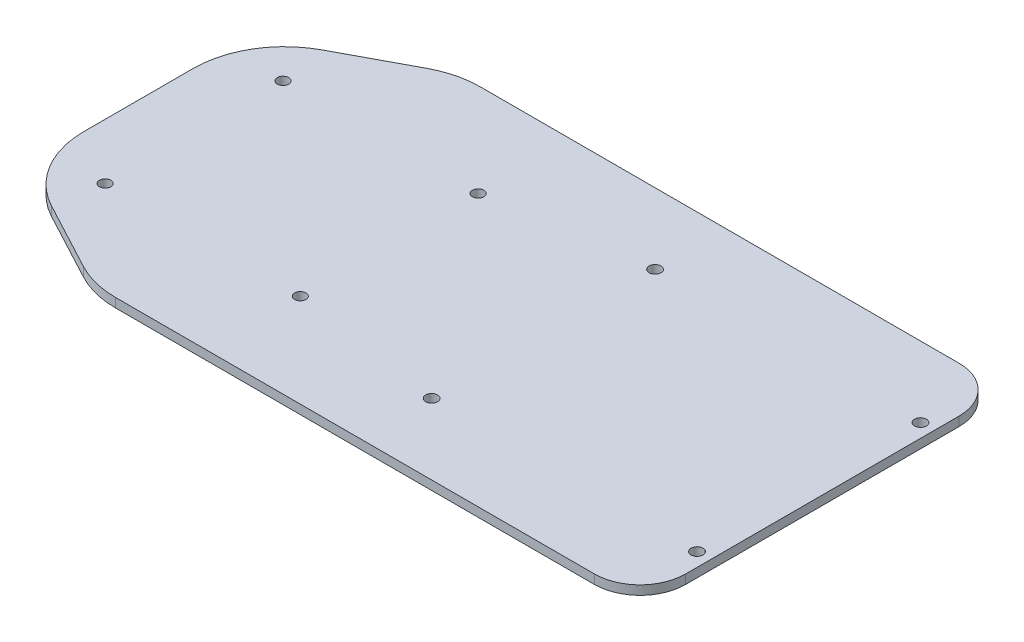
SolidWorks part; units mm, degrees
ref_plane "前视基准面" through (0, 0, 0) normal (0, 0, 1) x (1, 0, 0)
ref_plane "上视基准面" through (0, 0, 0) normal (0, 1, 0) x (1, 0, 0)
ref_plane "右视基准面" through (0, 0, 0) normal (1, 0, 0) x (0, 0, -1)
other "Configuration Table"
sketch "草图1" plane through (0, 0, 0) normal (0, 1, 0) x (1, 0, 0)
  line L0 (-41.4, 52.9432) -> (-41.4, -59.5525) construction
  line L1 (-75, -40) -> (75, -40)
  line L2 (-75, -40) -> (-75, 40)
  line L3 (-75, 40) -> (75, 40)
  line L4 (75, -40) -> (75, 40)
  line L5 (-75, -40) -> (75, 40) construction
  line L6 (-75, 40) -> (75, -40) construction
  line L7 (-75, 0) -> (32.4957, 0) construction
  circle A0 centre (-62.8, 19.5) radius 1.25
  circle A1 centre (-20, 19.5) radius 1.25
  circle A2 centre (-20, -19.5) radius 1.25
  circle A3 centre (-62.8, -19.5) radius 1.25
  point P0 (0, 0)
  point P14 (-18.5886, 20.7229)
  point P19 (-21.0671, 21.6867)
  point P20 (-24.6622, 19.5)
  dimension "D3" = 42.8
  dimension "D5" = 2.5
  dimension "D1" = 80
  dimension "D2" = 150
  dimension "D4" = 39
  dimension "D6" = 42.8
  dimension "D7" = 95
extrude "凸台-拉伸1" add sketch "草图1" along normal blind 2
sketch "草图2" plane through (0, 2, 0) normal (0, 1, 0) x (1, 0, 0)
  line L0 (-75, 0) -> (82.1354, 0) construction
  line L2 (42.9, 0) -> (42.9, 53.5496) construction
  line L3 (75, -40) -> (75, 40) construction
  circle A0 centre (13.8, 24.5) radius 1.3
  circle A1 centre (72, 24.5) radius 1.3
  circle A2 centre (13.8, -24.5) radius 1.3
  circle A3 centre (72, -24.5) radius 1.3
  dimension "D2" = 2.6
  dimension "D1" = 58.2
  dimension "D3" = 49
  dimension "D4" = 58.2
  dimension "D5" = 3
extrude "切除-拉伸1" cut sketch "草图2" against normal blind 2
sketch "草图3" plane through (0, 2, 0) normal (0, 1, 0) x (1, 0, 0)
  line L0 (0, 0) -> (90.8282, 0) construction
  line L1 (-75, 40) -> (-45, 40)
  line L2 (75, 40) -> (-75, 40) construction
  line L3 (-45, 40) -> (-75, 24)
  line L4 (-75, 40) -> (-75, -40) construction
  line L5 (-75, 24) -> (-75, 40)
  line L6 (-45, -40) -> (-75, -24)
  line L7 (-75, -40) -> (-45, -40)
  line L8 (-75, -24) -> (-75, -40)
  dimension "D1" = 30
  dimension "D2" = 16
extrude "切除-拉伸2" cut sketch "草图3" against normal blind 2
fillet "圆角1" radius 20 4 edges at (-45, 1, -40) (-75, 1, -24) (-45, 1, 40) (-75, 1, 24)
fillet "圆角2" radius 10 2 edges at (75, 1, -40) (75, 1, 40)
